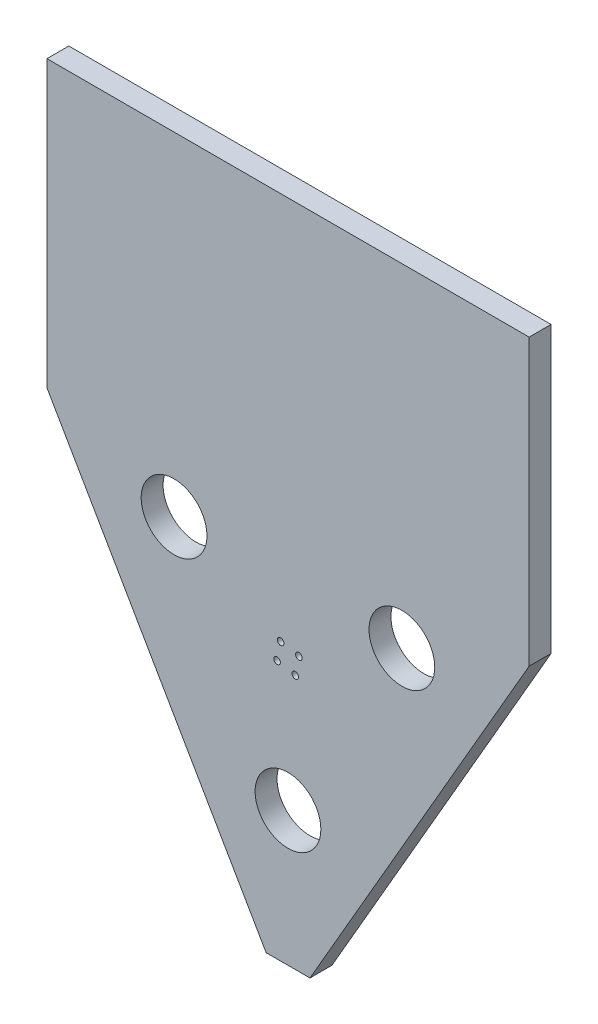
SolidWorks part; units mm, degrees
ref_plane "Front Plane" through (0, 0, 0) normal (0, 0, 1) x (1, 0, 0)
ref_plane "Top Plane" through (0, 0, 0) normal (0, 1, 0) x (1, 0, 0)
ref_plane "Right Plane" through (0, 0, 0) normal (1, 0, 0) x (0, 0, -1)
sketch "Sketch5" plane through (0, 0, 0) normal (0, 0, 1) x (1, 0, 0)
  line L0 (-349.7763, -150.6062) -> (-449.7763, -323.8113)
  line L1 (-449.7763, -323.8113) -> (-469.7763, -323.8113)
  line L2 (-469.7763, -323.8113) -> (-569.7763, -150.6062)
  line L8 (-569.7763, -150.6062) -> (-569.7763, -20.6062)
  line L9 (-569.7763, -20.6062) -> (-349.7763, -20.6062)
  line L10 (-349.7763, -150.6062) -> (-349.7763, -20.6062)
  circle A0 centre (-407.8463, -172.5859) radius 15
  circle A1 centre (-459.8079, -202.5859) radius 10
  circle A2 centre (-511.7694, -172.5859) radius 15
  circle A3 centre (-459.8079, -262.5859) radius 15
  circle A4 centre (-463.1498, -197.6028) radius 1.5
  circle A5 centre (-454.8248, -199.244) radius 1.5
  circle A6 centre (-456.4659, -207.5691) radius 1.5
  circle A7 centre (-464.791, -205.9279) radius 1.5
  point P6 (-459.8079, -202.5859)
  point P7 (-459.7763, -323.8113)
  point P19 (-459.8079, -202.5859)
  point P21 (-459.8079, -182.9304)
  point P30 (-459.8079, -202.5859)
  dimension "D5" = 60
  dimension "D6" = 20
  dimension "D16" = 120
  dimension "D3" = 30
  dimension "D7" = 3
  dimension "D8" = 3
  dimension "D1" = 200
  dimension "D2" = 60
  dimension "D4" = 60
  dimension "D9" = 6
  dimension "D10" = 4
  dimension "D11" = 130
  dimension "D12" = 220
  dimension "D13" = 20
  dimension "D14" = 200
  dimension "D15" = 120
  dimension "D17" = 61.2253
  dimension "D18" = 150
  dimension "D19" = 150
  dimension "D20" = 303.2051
  dimension "D21" = 121.2253
extrude "Boss-Extrude1" add sketch "Sketch5" along normal blind 10 contours L0 L10 L9 L8 L2 L1 A3 A2 A1 A0 | A1 A7 A6 A5 A4
